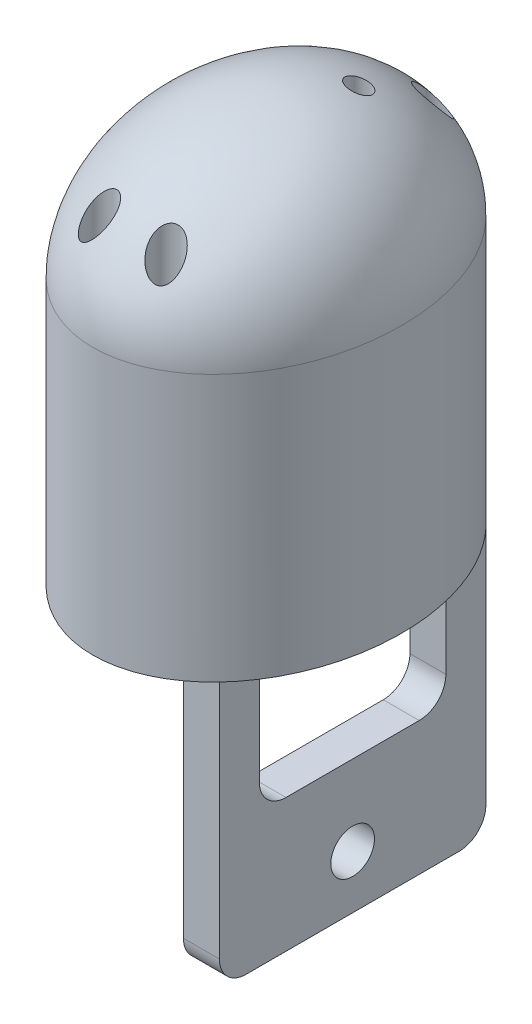
SolidWorks part; units mm, degrees
ref_plane "Front Plane" through (0, 0, 0) normal (0, 0, 1) x (1, 0, 0)
ref_plane "Top Plane" through (0, 0, 0) normal (0, 1, 0) x (1, 0, 0)
ref_plane "Right Plane" through (0, 0, 0) normal (1, 0, 0) x (0, 0, -1)
sketch "Sketch1" plane through (0, 0, 0) normal (0, 1, 0) x (1, 0, 0)
  line L0 (0, 0) -> (6.5, 0) construction
  line L1 (6.5, 0) -> (3.8, 0)
  line L2 (6.5, 0) -> (6.5, 20)
  line L3 (6.5, 20) -> (3.8, 20)
  line L4 (3.8, 0) -> (3.8, 20)
  line L5 (6.5, 0) -> (3.8, 20) construction
  line L6 (6.5, 20) -> (3.8, 0) construction
  point P0 (5.15, 10)
  dimension "D1" = 6.5
  dimension "D2" = 2.7
  dimension "D3" = 20
extrude "Boss-Extrude1" add sketch "Sketch1" along normal blind 20
sketch "Sketch4" plane through (0, 20, 0) normal (0, 1, 0) x (1, 0, 0)
  line L0 (0, -3) -> (0, 23) construction
  ellipse E0 centre (0, 10) end of major axis (0, 23) minor radius 10.1726
  dimension "D1" = 26
extrude "Boss-Extrude2" add sketch "Sketch4" along normal blind 20
sketch "Sketch5" plane through (0, 40, 0) normal (0, 1, 0) x (1, 0, 0)
  line L0 (0, 23) -> (0, -3)
  ellipse E0 centre (0, 10) end of major axis (0, -3) minor radius 10.1726 (0, 23) -> (0, -3) cw
  ellipse E1 centre (0, 10) end of major axis (0, 23) minor radius 10.1726 construction
revolve "Revolve1" add sketch "Sketch5" angle 180 about L0
sketch "Sketch6" plane through (3.8, 0, 0) normal (-1, 0, 0) x (0, 0, 1)
  line L0 (-10, 0) -> (-10, 20) construction
  line L1 (-20, 0) -> (0, 0) construction
  line L2 (-23, 20) -> (3, 20) construction
  line L3 (-20, 20) -> (-20, 0) construction
  line L4 (-3, 10) -> (-17, 10)
  line L5 (-3, 10) -> (-3, 20)
  line L6 (-3, 20) -> (-17, 20)
  line L7 (-17, 10) -> (-17, 20)
  line L8 (-3, 10) -> (-17, 20) construction
  line L9 (-3, 20) -> (-17, 10) construction
  circle A0 centre (-10, 4) radius 1.64
  point P8 (-10, 15)
  dimension "D1" = 3.28
  dimension "D2" = 4
  dimension "D3" = 10
  dimension "D4" = 3
extrude "Cut-Extrude1" cut sketch "Sketch6" against normal up to next
fillet "Fillet1" radius 2 4 edges at (5.15, 0, 0) (5.15, 0, -20) (5.15, 10, -17) (5.15, 10, -3)
sketch "Sketch10" plane through (0, 20, 0) normal (0, -1, 0) x (1, 0, 0)
  line L0 (0, 0) -> (0, -20)
  line L1 (0, 3) -> (0, -23) construction
  ellipse E0 centre (0, -10) end of major axis (0, -23) minor radius 10.1726 (6.5, 0) -> (6.5, -20) ccw construction
  ellipse E2 centre (0, -10) end of major axis (0, -20) minor radius 5.3211 (0, -20) -> (0, 0) ccw
  dimension "D1" = 3
  dimension "D2" = 3
revolve "Cut-Revolve5" cut sketch "Sketch10" angle 180 about L0
sketch "Sketch11" plane through (0, 20, 0) normal (0, -1, 0) x (-1, 0, 0)
  line L0 (-3.8, 3) -> (-3.8, 0) construction
  line L1 (-6.5, 17) -> (-3.8, 17) construction
  line L2 (-3.8, 18) -> (-3.8, 2) construction
  line L3 (0, 23) -> (0, -3) construction
  line L4 (-10.1726, 10) -> (10.1726, 10) construction
  circle A0 centre (-2.13, 14.83) radius 0.86
  circle A1 centre (-2.5, 20) radius 1.125
  circle A2 centre (2.5, 20) radius 1.125
  circle A5 centre (-2.5, 0) radius 1.125
  circle A6 centre (2.5, 0) radius 1.125
  ellipse E0 centre (0, 10) end of major axis (0, 23) minor radius 10.1726 (-6.5, 20) -> (-6.5, 0) ccw construction
  ellipse E2 centre (0, 10) end of major axis (0, 20) minor radius 5.3211 (-3.8, 3) -> (-3.8, 17) ccw construction
  ellipse E3 centre (0, 10) end of major axis (0, 23) minor radius 10.1726 (-6.5, 0) -> (-6.5, 20) ccw construction
  point P4 (-3.8, 1.5)
  dimension "D1" = 1.72
  dimension "D4" = 2.25
  dimension "D2" = 1.67
  dimension "D3" = 2.17
  dimension "D5" = 1.3
  dimension "D6" = 10
extrude "Cut-Extrude5" cut sketch "Sketch11" against normal offset from surface (29.9871 mm away) 1
